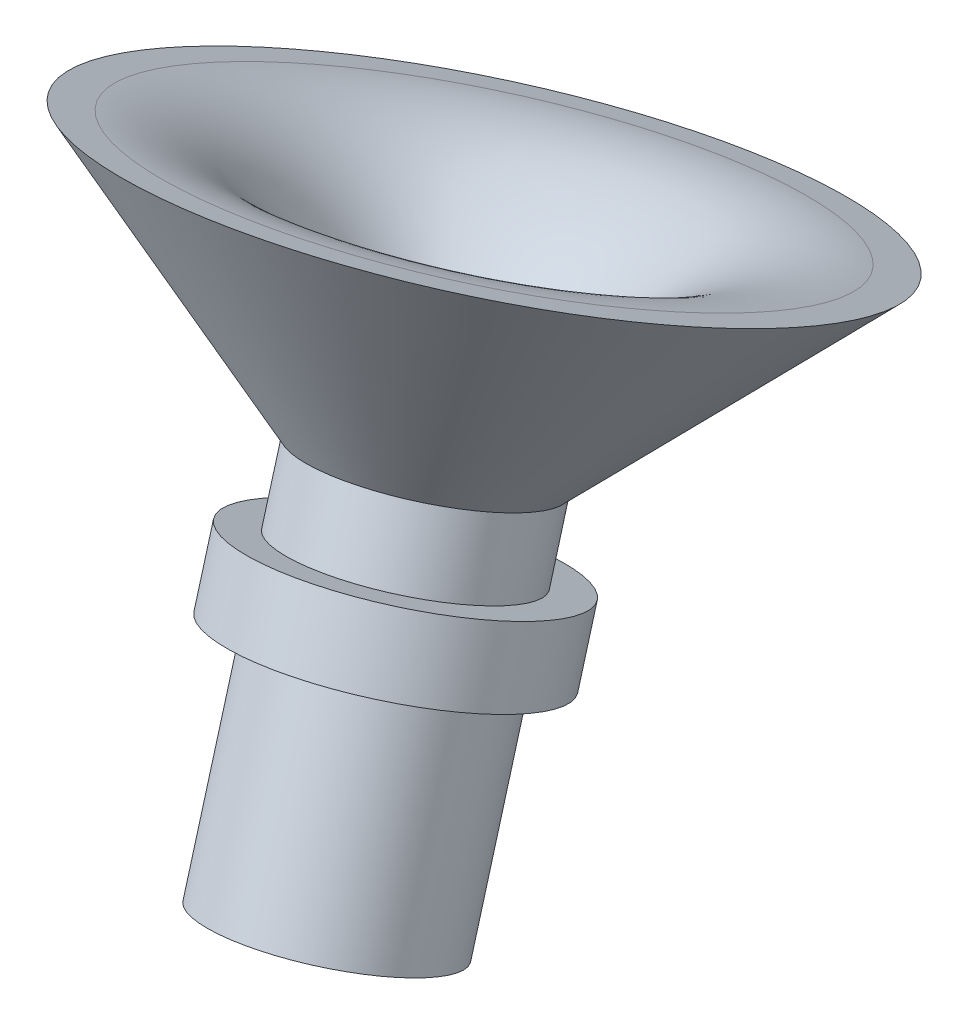
SolidWorks part; units mm, degrees
other "Inlet Fairlead Liner"
other "Inlet Fairlead Liner Left"
ref_plane "Front Plane" through (0, 0, 0) normal (0, 0, 1) x (1, 0, 0)
ref_plane "Top Plane" through (0, 0, 0) normal (0, 1, 0) x (1, 0, 0)
ref_plane "Right Plane" through (0, 0, 0) normal (1, 0, 0) x (0, 0, -1)
sketch3d "Inlet Fairlead Liner Feature axis line"
  line L0 (-17.2536, -35.9152, 3.8742) -> (-19.3297, -54.2359, -3.8742) construction
ref_axis "Inlet Fairlead Liner Feature axis" through (-17.2536, -35.9152, 3.8742) along (-0.1038, -0.916, -0.3874)
sketch3d "Inlet Fairlead Liner Profile datum points"
  point P0 (-18.2917, -45.0756, 0)
  point P1 (-27.9509, -45.0756, 2.5882)
  point P2 (-19.3297, -54.2359, -3.8742)
ref_plane "Inlet Fairlead Liner Profile plane" through (3.2582, -5.512, 12.1598) normal (0.2371, -0.4011, 0.8848) x (0.9715, 0.0979, -0.2159)
sketch "Inlet Fairlead Liner Profile" plane through (3.2582, -5.512, 12.1598) normal (0.2371, -0.4011, 0.8848) x (0.9715, 0.0979, -0.2159)
  line L0 (-23.152, -30.8928) -> (-23.5794, -34.8699)
  line L1 (-23.5794, -34.8699) -> (-22.6349, -34.9714)
  line L2 (-22.6349, -34.9714) -> (-23.0623, -38.9485)
  line L3 (-30.8771, -46.1547) -> (-31.8714, -46.0478)
  line L4 (-31.8714, -46.0478) -> (-25.1651, -40.734)
  line L5 (-25.1651, -40.734) -> (-24.9514, -38.7454)
  line L6 (-24.9514, -38.7454) -> (-25.9457, -38.6386)
  line L7 (-25.9457, -38.6386) -> (-25.732, -36.65)
  line L8 (-25.732, -36.65) -> (-24.7377, -36.7569)
  line L9 (-24.7377, -36.7569) -> (-24.0966, -30.7912)
  line L10 (-24.0966, -30.7912) -> (-23.152, -30.8928)
  arc A0 (-30.8771, -46.1547) -> (-24.2703, -40.8302) centre (-30.2359, -40.189) ccw
  spline S0 degree 3 poles (-23.0623, -38.9485) (-23.1335, -39.6113) (-24.1991, -40.1673) (-24.2703, -40.8302) knots 0 0 0 0 1 1 1 1
revolve "Inlet Fairlead Liner Feature" add sketch "Inlet Fairlead Liner Profile" angle 360 about axis through (-17.2536, -35.9152, 3.8742) along (-0.1038, -0.916, -0.3874)
sketch3d "Mirror1 profile datum points"
  point P0 (0, 0, 0)
  point P1 (10, 0, 0)
  point P2 (0, 0, 10)
ref_plane "Mirror1 profile plane" through (0, 0, 0) normal (0, -1, 0) x (-1, 0, 0)
mirror "Mirror1" about plane through (0, 0, 0) normal (0, -1, 0) of bodies 101
delete or keep bodies "Remove1" type delete bodies bodies 101
